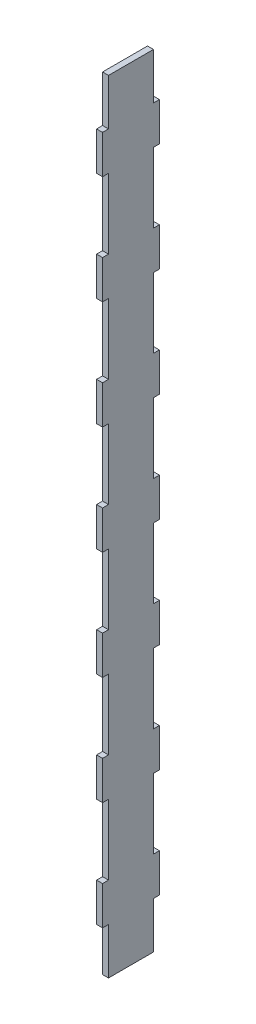
SolidWorks part; units mm, degrees
ref_plane "Plan de face" through (0, 0, 0) normal (0, 0, 1) x (1, 0, 0)
ref_plane "Plan de dessus" through (0, 0, 0) normal (0, 1, 0) x (1, 0, 0)
ref_plane "Plan de droite" through (0, 0, 0) normal (1, 0, 0) x (0, 0, -1)
sketch "Esquisse1" plane through (0, 0, 0) normal (0, 0, 1) x (1, 0, 0)
  line L0 (-43, 163.6) -> (-43, 163.346)
  line L1 (-39.825, 163.6) -> (-39.825, 163.346)
  line L2 (-43, 183.6) -> (-43, 183.854)
  line L3 (-39.825, 183.6) -> (-39.825, 183.854)
  line L8 (-39.571, 183.854) -> (-43.254, 183.854) construction
  line L9 (-43.254, 163.346) -> (-39.571, 163.346) construction
  line L10 (-43, 125.7333) -> (-43, 125.9873)
  line L11 (-39.825, 125.7333) -> (-39.825, 125.9873)
  line L12 (-43, 105.7333) -> (-43, 105.4793)
  line L13 (-39.825, 105.7333) -> (-39.825, 105.4793)
  line L14 (-39.571, 125.9873) -> (-43.254, 125.9873) construction
  line L15 (-43.254, 105.4793) -> (-39.571, 105.4793) construction
  line L16 (-43, 67.8667) -> (-43, 68.1207)
  line L17 (-39.825, 67.8667) -> (-39.825, 68.1207)
  line L18 (-39.825, 47.8667) -> (-39.825, 47.6127)
  line L19 (-43, 47.8667) -> (-43, 47.6127)
  line L20 (-43.254, 47.6127) -> (-39.571, 47.6127) construction
  line L21 (-39.571, 68.1207) -> (-43.254, 68.1207) construction
  line L22 (-43, 10) -> (-43, 10.254)
  line L23 (-39.825, 10) -> (-39.825, 10.254)
  line L24 (-43, -10) -> (-43, -10.254)
  line L25 (-39.825, -10) -> (-39.825, -10.254)
  line L26 (-43.254, -10.254) -> (-39.571, -10.254) construction
  line L27 (-39.571, 10.254) -> (-43.254, 10.254) construction
  line L92 (-43, -183.6) -> (-39.825, -183.6) construction
  line L93 (-43, -163.6) -> (-43, -183.6) construction
  line L94 (-39.825, -183.6) -> (-39.825, -163.6) construction
  line L95 (-39.825, -163.6) -> (-43, -163.6) construction
  line L96 (-43, -125.7333) -> (-39.825, -125.7333) construction
  line L97 (-43, -105.7333) -> (-43, -125.7333) construction
  line L98 (-39.825, -125.7333) -> (-39.825, -105.7333) construction
  line L99 (-39.825, -105.7333) -> (-43, -105.7333) construction
  line L100 (-43, -67.8667) -> (-39.825, -67.8667) construction
  line L101 (-43, -47.8667) -> (-43, -67.8667) construction
  line L102 (-39.825, -67.8667) -> (-39.825, -47.8667) construction
  line L103 (-39.825, -47.8667) -> (-43, -47.8667) construction
  line L104 (-43, -10) -> (-39.825, -10) construction
  line L105 (-39.825, 10) -> (-43, 10) construction
  line L106 (-43, 10) -> (-43, -10) construction
  line L107 (-39.825, -10) -> (-39.825, 10) construction
  line L108 (-43, 47.8667) -> (-39.825, 47.8667) construction
  line L109 (-43, 67.8667) -> (-43, 47.8667) construction
  line L110 (-39.825, 47.8667) -> (-39.825, 67.8667) construction
  line L111 (-39.825, 67.8667) -> (-43, 67.8667) construction
  line L112 (-43, 105.7333) -> (-39.825, 105.7333) construction
  line L113 (-39.825, 105.7333) -> (-39.825, 125.7333) construction
  line L114 (-43, 125.7333) -> (-43, 105.7333) construction
  line L115 (-39.825, 125.7333) -> (-43, 125.7333) construction
  line L116 (-43, 163.6) -> (-39.825, 163.6) construction
  line L117 (-39.825, 183.6) -> (-43, 183.6) construction
  line L118 (-39.825, 163.6) -> (-39.825, 183.6) construction
  line L119 (-43, 183.6) -> (-43, 163.6) construction
  line L120 (-43, -183.6) -> (-39.825, -183.6) construction
  line L121 (-43, -163.6) -> (-43, -183.6)
  line L122 (-39.825, -183.6) -> (-39.825, -163.6)
  line L123 (-39.825, -163.6) -> (-43, -163.6) construction
  line L124 (-43, -125.7333) -> (-39.825, -125.7333) construction
  line L125 (-43, -105.7333) -> (-43, -125.7333)
  line L126 (-39.825, -125.7333) -> (-39.825, -105.7333)
  line L127 (-39.825, -105.7333) -> (-43, -105.7333) construction
  line L128 (-43, -67.8667) -> (-39.825, -67.8667) construction
  line L129 (-43, -47.8667) -> (-43, -67.8667)
  line L130 (-39.825, -67.8667) -> (-39.825, -47.8667)
  line L131 (-39.825, -47.8667) -> (-43, -47.8667) construction
  line L132 (-43, -10) -> (-39.825, -10) construction
  line L133 (-39.825, 10) -> (-43, 10) construction
  line L134 (-43, 10) -> (-43, -10)
  line L135 (-39.825, -10) -> (-39.825, 10)
  line L136 (-43, 47.8667) -> (-39.825, 47.8667) construction
  line L137 (-43, 67.8667) -> (-43, 47.8667)
  line L138 (-39.825, 47.8667) -> (-39.825, 67.8667)
  line L139 (-39.825, 67.8667) -> (-43, 67.8667) construction
  line L140 (-43, 105.7333) -> (-39.825, 105.7333) construction
  line L141 (-39.825, 105.7333) -> (-39.825, 125.7333)
  line L142 (-43, 125.7333) -> (-43, 105.7333)
  line L143 (-39.825, 125.7333) -> (-43, 125.7333) construction
  line L144 (-43, 163.6) -> (-39.825, 163.6) construction
  line L145 (-39.825, 183.6) -> (-43, 183.6) construction
  line L146 (-39.825, 163.6) -> (-39.825, 183.6)
  line L147 (-43, 183.6) -> (-43, 163.6)
  line L148 (-43, -183.854) -> (-39.825, -183.854)
  line L150 (-39.825, -163.346) -> (-43, -163.346)
  line L152 (-43, -125.9873) -> (-39.825, -125.9873)
  line L154 (-39.825, -105.4793) -> (-43, -105.4793)
  line L156 (-43, -68.1207) -> (-39.825, -68.1207)
  line L158 (-39.825, -47.6127) -> (-43, -47.6127)
  line L160 (-43, -10.254) -> (-39.825, -10.254)
  line L162 (-39.825, 10.254) -> (-43, 10.254)
  line L164 (-43, 47.6127) -> (-39.825, 47.6127)
  line L166 (-39.825, 68.1207) -> (-43, 68.1207)
  line L168 (-43, 105.4793) -> (-39.825, 105.4793)
  line L170 (-39.825, 125.9873) -> (-43, 125.9873)
  line L172 (-43, 163.346) -> (-39.825, 163.346)
  line L174 (-39.825, 183.854) -> (-43, 183.854)
  line L176 (-43.254, 183.854) -> (-43.254, 163.346) construction
  line L177 (-39.571, 163.346) -> (-39.571, 183.854) construction
  line L178 (-43.254, 125.9873) -> (-43.254, 105.4793) construction
  line L179 (-39.571, 105.4793) -> (-39.571, 125.9873) construction
  line L180 (-43.254, 68.1207) -> (-43.254, 47.6127) construction
  line L181 (-39.571, 47.6127) -> (-39.571, 68.1207) construction
  line L182 (-43.254, 10.254) -> (-43.254, -10.254) construction
  line L183 (-39.571, -10.254) -> (-39.571, 10.254) construction
  line L184 (-43, -47.8667) -> (-43, -47.6127)
  line L185 (-39.825, -47.8667) -> (-39.825, -47.6127)
  line L186 (-43, -67.8667) -> (-43, -68.1207)
  line L187 (-39.825, -67.8667) -> (-39.825, -68.1207)
  line L188 (-43.254, -68.1207) -> (-39.571, -68.1207) construction
  line L189 (-43.254, -47.6127) -> (-43.254, -68.1207) construction
  line L190 (-39.571, -68.1207) -> (-39.571, -47.6127) construction
  line L191 (-39.571, -47.6127) -> (-43.254, -47.6127) construction
  line L192 (-43, -105.7333) -> (-43, -105.4793)
  line L193 (-39.825, -105.7333) -> (-39.825, -105.4793)
  line L194 (-43, -125.7333) -> (-43, -125.9873)
  line L195 (-39.825, -125.7333) -> (-39.825, -125.9873)
  line L196 (-43.254, -125.9873) -> (-39.571, -125.9873) construction
  line L197 (-43.254, -105.4793) -> (-43.254, -125.9873) construction
  line L198 (-39.571, -125.9873) -> (-39.571, -105.4793) construction
  line L199 (-39.571, -105.4793) -> (-43.254, -105.4793) construction
  line L200 (-43, -183.6) -> (-43, -183.854)
  line L201 (-39.825, -183.6) -> (-39.825, -183.854)
  line L202 (-43, -163.6) -> (-43, -163.346)
  line L203 (-39.825, -163.6) -> (-39.825, -163.346)
  line L204 (-39.571, -163.346) -> (-43.254, -163.346) construction
  line L205 (-43.254, -163.346) -> (-43.254, -183.854) construction
  line L206 (-39.571, -183.854) -> (-39.571, -163.346) construction
  line L207 (-43.254, -183.854) -> (-39.571, -183.854) construction
  dimension "D1" = 0.254
extrude "Boss.-Extru.1" add sketch "Esquisse1" along normal blind 27.175 and the other way up to surface (3.175 mm away)
sketch "Esquisse2" plane through (0, -10.254, 0) normal (0, -1, 0) x (1, 0, 0)
  line L1 (-43, 24) -> (-39.825, 24)
  line L2 (-43, 24) -> (-43, 0)
  line L3 (-43, 0) -> (-39.825, 0)
  line L4 (-39.825, 24) -> (-39.825, 0)
  line L6 (-43, 27.175) -> (-39.825, 27.175) construction
  line L7 (-90, 0) -> (90, 0) construction
  line L8 (-43, -3.175) -> (-43, 27.175) construction
  line L9 (-39.825, -3.175) -> (-39.825, 27.175) construction
  dimension "D1" = 3.175
extrude "Boss.-Extru.2" add sketch "Esquisse2" along normal up to surface (198.346 mm away) and the other way up to surface (218.854 mm away)
ref_plane "Plan1" through (0, 0, 12) normal (0, 0, 1) x (1, 0, 0)
equation "\"D1@Esquisse2\"=\"EpaisseurBois@corps_bottom-1.Part\""
